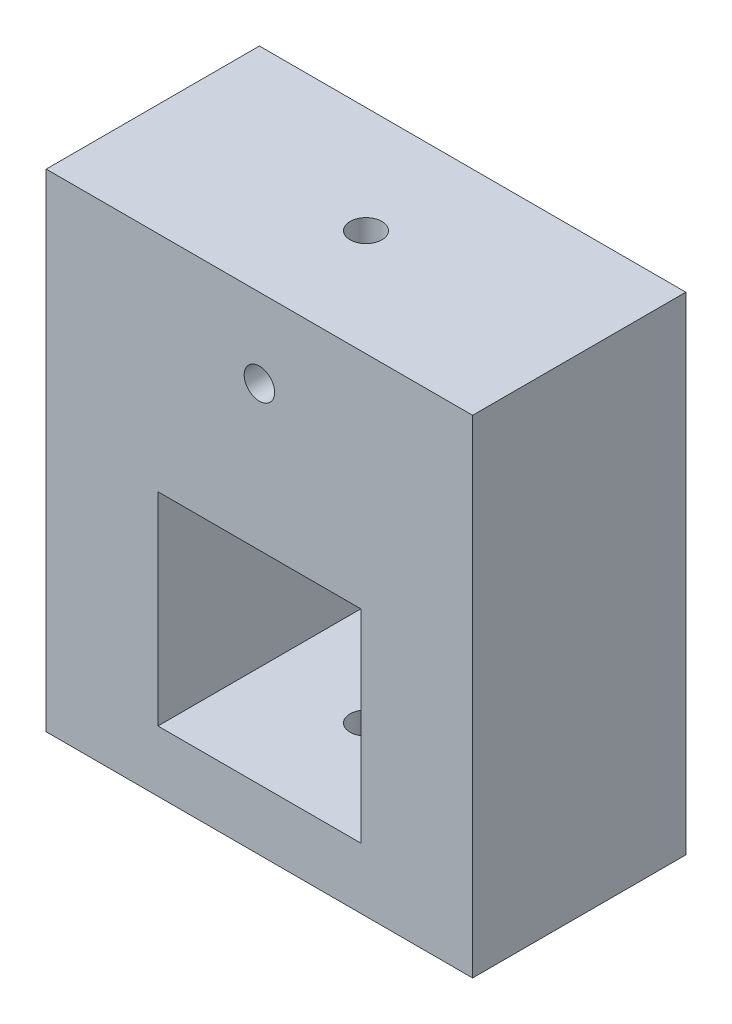
SolidWorks part; units mm, degrees
ref_plane "Front Plane" through (0, 0, 0) normal (0, 0, 1) x (1, 0, 0)
ref_plane "Top Plane" through (0, 0, 0) normal (0, 1, 0) x (1, 0, 0)
ref_plane "Right Plane" through (0, 0, 0) normal (1, 0, 0) x (0, 0, -1)
sketch "Sketch1" plane through (0, 0, 0) normal (0, 1, 0) x (1, 0, 0)
  line L1 (-44.45, -22.225) -> (44.45, -22.225)
  line L2 (-44.45, -22.225) -> (-44.45, 22.225)
  line L3 (-44.45, 22.225) -> (44.45, 22.225)
  line L4 (44.45, -22.225) -> (44.45, 22.225)
  line L5 (-44.45, -22.225) -> (44.45, 22.225) construction
  line L6 (-44.45, 22.225) -> (44.45, -22.225) construction
  circle A0 centre (0, 0) radius 3.3231
  point P0 (0, 0)
  dimension "D3" = 6.6462
  dimension "D1" = 44.45
  dimension "D2" = 88.9
extrude "Boss-Extrude1" add sketch "Sketch1" along normal blind 101.6
sketch "Sketch2" plane through (0, 0, 22.225) normal (0, 0, 1) x (1, 0, 0)
  line L0 (0, 101.6) -> (0, 0) construction
  line L1 (-44.45, 101.6) -> (44.45, 101.6) construction
  line L2 (-44.45, 0) -> (44.45, 0) construction
  line L3 (44.45, 0) -> (-44.45, 0) construction
  line L4 (21.15, 55) -> (-21.15, 55)
  line L5 (21.15, 55) -> (21.15, 12.7)
  line L6 (21.15, 12.7) -> (-21.15, 12.7)
  line L7 (-21.15, 55) -> (-21.15, 12.7)
  line L8 (21.15, 55) -> (-21.15, 12.7) construction
  line L9 (21.15, 12.7) -> (-21.15, 55) construction
  circle A1 centre (0, 85.09) radius 3.175
  point P5 (0, 33.85)
  dimension "D1" = 42.3
  dimension "D2" = 42.3
  dimension "D3" = 6.35
  dimension "D4" = 85.09
  dimension "D5" = 12.7
extrude "Cut-Extrude1" cut sketch "Sketch2" against normal through all
